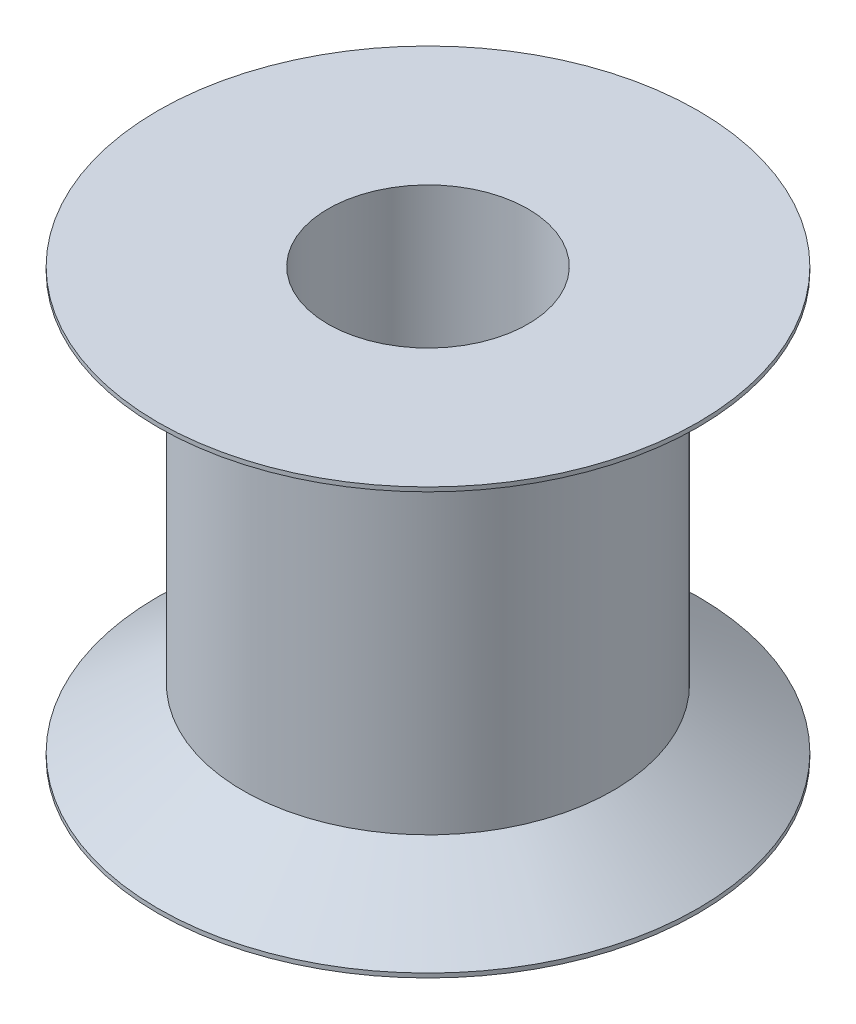
SolidWorks part; units mm, degrees
material "Custom Plastic"
ref_plane "Front Plane" through (0, 0, 0) normal (0, 0, 1) x (1, 0, 0)
ref_plane "Top Plane" through (0, 0, 0) normal (0, 1, 0) x (1, 0, 0)
ref_plane "Right Plane" through (0, 0, 0) normal (1, 0, 0) x (0, 0, -1)
sketch "Sketch1" plane through (0, 0, 0) normal (1, 0, 0) x (0, 0, -1)
  line L0 (2.35, 5) -> (2.35, -5)
  line L1 (2.35, -5) -> (6.35, -5)
  line L2 (6.35, -5) -> (6.35, -4.9)
  line L3 (6.35, -4.9) -> (4.35, -3.5)
  line L4 (4.35, -3.5) -> (4.35, 3.5)
  line L5 (4.35, 3.5) -> (6.35, 4.9)
  line L6 (6.35, 4.9) -> (6.35, 5)
  line L7 (6.35, 5) -> (2.35, 5)
  line L8 (0, 0) -> (0, 9.7759) construction
  point P2 (2.35, 0)
  dimension "D1" = 2.35
  dimension "D2" = 4
  dimension "D3" = 4.35
  dimension "D4" = 1.5
  dimension "D5" = 1.5
  dimension "D6" = 0.1
  dimension "D7" = 0.1
  dimension "D8" = 4
  dimension "D9" = 10
revolve "Revolve1" add sketch "Sketch1" angle 360 about L8
